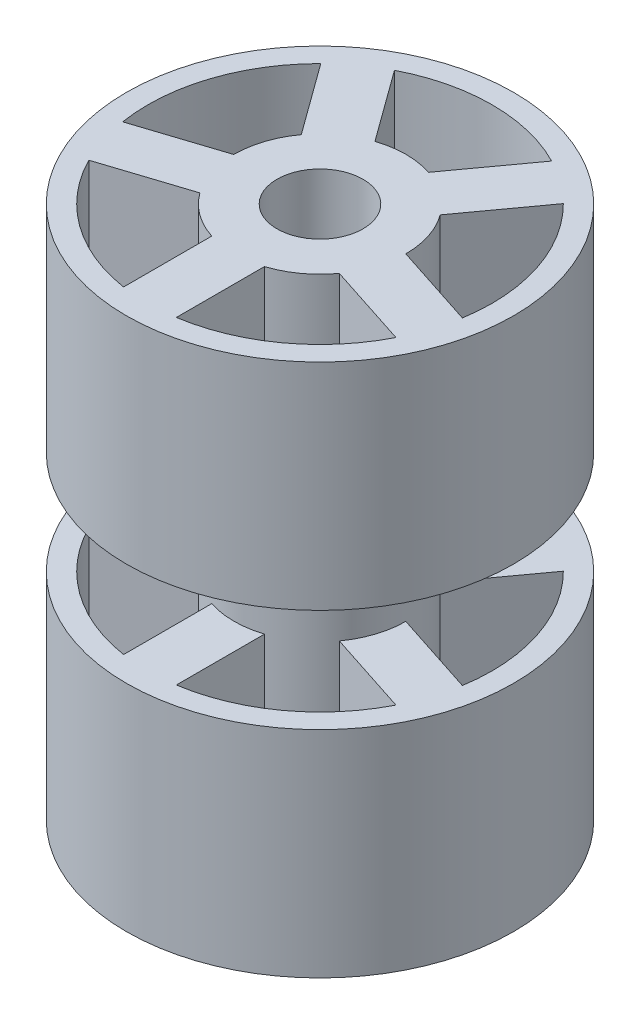
SolidWorks part; units mm, degrees
material "ABS"
ref_plane "Front" through (0, 0, 0) normal (0, 0, 1) x (1, 0, 0)
ref_plane "Top" through (0, 0, 0) normal (0, 1, 0) x (1, 0, 0)
ref_plane "Right" through (0, 0, 0) normal (1, 0, 0) x (0, 0, -1)
sketch "Sketch1" plane through (0, 0, 0) normal (1, 0, 0) x (0, 0, -1)
  line L0 (0, 0) -> (0, 271.9184) construction
  line L1 (5, 0) -> (10, 0)
  line L2 (22.5, 0) -> (22.5, 25)
  line L3 (22.5, 25) -> (20, 25)
  line L5 (22.5, 37) -> (22.5, 62)
  line L6 (22.5, 62) -> (20, 62)
  line L7 (20, 25) -> (20, 0)
  line L8 (20, 62) -> (20, 37)
  line L9 (5, 25) -> (5, 0)
  line L10 (5, 0) -> (10, 0)
  line L11 (10, 0) -> (10, 25)
  line L13 (5, 37) -> (5, 62)
  line L14 (5, 62) -> (10, 62)
  line L15 (10, 62) -> (10, 37)
  line L17 (10, 62) -> (5, 62)
  line L18 (20, 37) -> (22.5, 37)
  line L20 (20, 0) -> (22.5, 0)
  line L21 (10, 25) -> (10, 37)
  line L22 (5, 25) -> (5, 37)
  point P12 (22.5, 12.5)
  dimension "D1" = 25
  dimension "D2" = 2.5
  dimension "D3" = 2.5
  dimension "D4" = 10
  dimension "D5" = 5
  dimension "D6" = 5
  dimension "D7" = 10
  dimension "D8" = 10
  dimension "D9" = 12
  dimension "D10" = 10
revolve "Revolve1" add sketch "Sketch1" angle 360 about L0
sketch "Sketch2" plane through (0, 0, 0) normal (0, -1, 0) x (1, 0, 0)
  line L0 (-3.0654, 9.5186) -> (3.0654, 9.5186)
  line L1 (-3.0654, 9.5186) -> (-3.0654, 20.5186)
  line L2 (3.0654, 9.5186) -> (3.0654, 20.5186)
  line L3 (-3.0654, 20.5186) -> (3.0654, 20.5186)
  circle A0 centre (0, 0) radius 10 construction
  dimension "D1" = 11
extrude "Boss-Extrude1" add sketch "Sketch2" against normal blind 25
pattern_circular "CirPattern1" count 5 over 360 about axis through (0, 0, 0) along (0, 1, 0) of "Boss-Extrude1"
sketch "Sketch3" plane through (0, 62, 0) normal (0, 1, 0) x (-1, 0, 0)
  line L0 (-3.0654, 8.8639) -> (3.0654, 8.8639)
  line L1 (-3.0654, 8.8639) -> (-3.0654, 20.8639)
  line L2 (3.0654, 8.8639) -> (3.0654, 20.8639)
  line L3 (-3.0654, 20.8639) -> (3.0654, 20.8639)
  line L4 (-3.0654, 9.5186) -> (-3.0654, 19.7637) construction
  dimension "D1" = 12
extrude "Boss-Extrude2" add sketch "Sketch3" against normal blind 25 contours L2 L3 L1 L0
pattern_circular "CirPattern2" count 5 over 360 about axis through (0, 0, 0) along (0, 1, 0) of "Boss-Extrude2"
